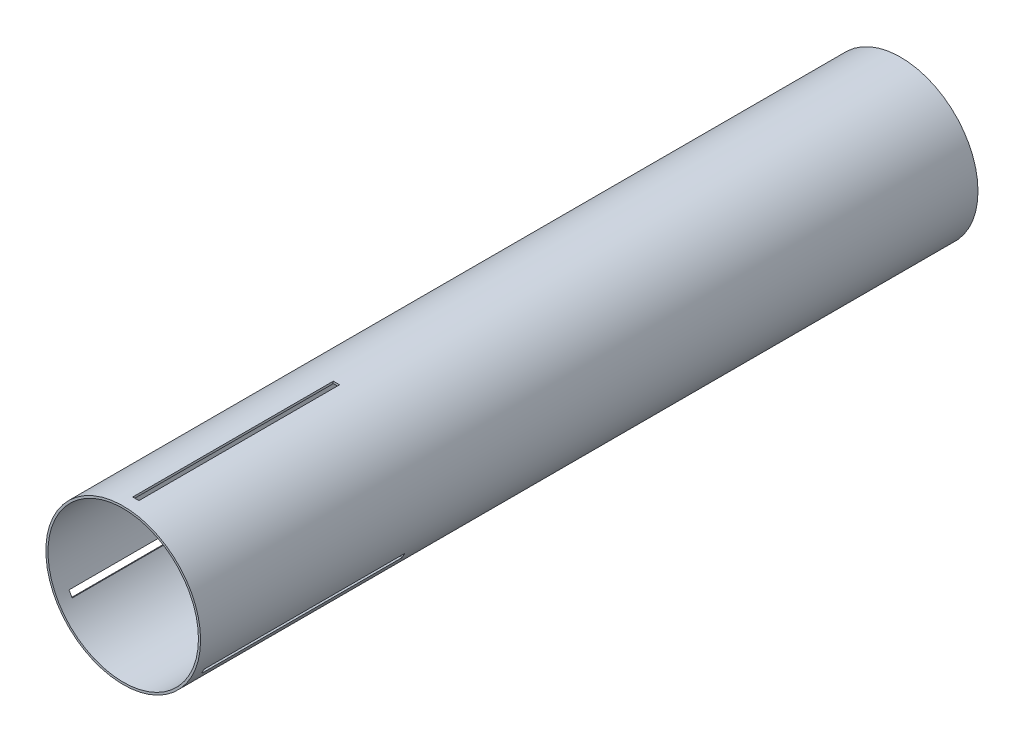
SolidWorks part; units mm, degrees
ref_plane "Plan de face" through (0, 0, 0) normal (0, 0, 1) x (1, 0, 0)
ref_plane "Plan de dessus" through (0, 0, 0) normal (0, 1, 0) x (1, 0, 0)
ref_plane "Plan de droite" through (0, 0, 0) normal (1, 0, 0) x (0, 0, -1)
sketch "Esquisse2" plane through (0, 0, 0) normal (0, 0, 1) x (1, 0, 0)
  circle A0 centre (0, 0) radius 78.359
  circle A1 centre (0, 0) radius 76.2
  dimension "D1" = 156.718
  dimension "D2" = 152.4
extrude "Boss.-Extru.1" add sketch "Esquisse2" along normal blind 787.4
sketch "Esquisse3" plane through (0, 0, 0) normal (0, 1, 0) x (1, 0, 0)
  line L0 (0, -787.4) -> (0, -774.7)
  line L1 (-78.359, -787.4) -> (78.359, -787.4) construction
  line L2 (0, -774.7) -> (0, -673.1)
  line L3 (0, -774.7) -> (-3.175, -774.7)
  line L5 (3.175, -571.5) -> (-3.175, -571.5)
  line L6 (3.175, -571.5) -> (3.175, -774.7)
  line L7 (3.175, -774.7) -> (-3.175, -774.7)
  line L8 (-3.175, -571.5) -> (-3.175, -774.7)
  line L9 (3.175, -571.5) -> (-3.175, -774.7) construction
  line L10 (3.175, -774.7) -> (-3.175, -571.5) construction
  dimension "D1" = 12.7
  dimension "D2" = 101.6
  dimension "D3" = 3.175
extrude "Enlèv. mat.-Extru.1" cut sketch "Esquisse3" along normal blind 153.416 contours L7 L6 L5 L8
pattern_circular "Répétition circulaire1" count 3 every 120 about axis through (0, 0, 0) along (0, 0, 1) of "Enlèv. mat.-Extru.1"
